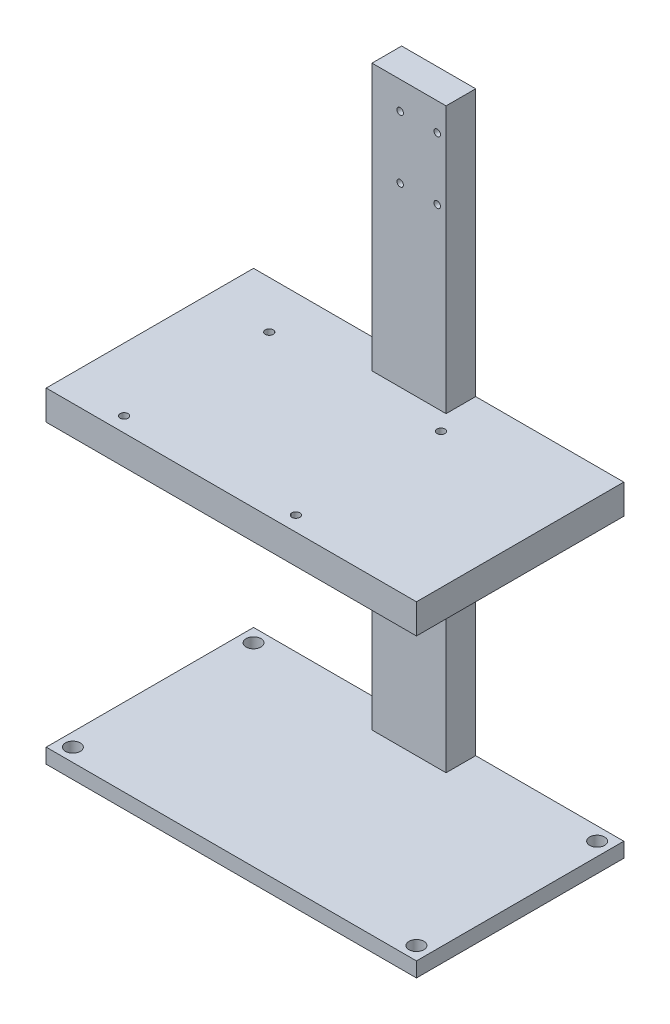
SolidWorks part; units mm, degrees
ref_plane "Front Plane" through (0, 0, 0) normal (0, 0, 1) x (1, 0, 0)
ref_plane "Top Plane" through (0, 0, 0) normal (0, 1, 0) x (1, 0, 0)
ref_plane "Right Plane" through (0, 0, 0) normal (1, 0, 0) x (0, 0, -1)
sketch "Sketch2" plane through (0, 0, 0) normal (0, 0, 1) x (1, 0, 0)
  line L1 (-80.8946, 1.3413) -> (-55.8946, 1.3413)
  line L2 (-80.8946, 1.3413) -> (-80.8946, -98.6587)
  line L3 (-80.8946, -98.6587) -> (-55.8946, -98.6587)
  line L4 (-55.8946, 1.3413) -> (-55.8946, -98.6587)
  line L5 (-80.8946, -98.6587) -> (-55.8946, -98.6587)
  line L6 (-80.8946, -98.6587) -> (-80.8946, -198.6587)
  line L7 (-80.8946, -198.6587) -> (-55.8946, -198.6587)
  line L8 (-130.8946, -88.6587) -> (-5.8946, -88.6587)
  line L9 (-130.8946, -88.6587) -> (-130.8946, -98.6587)
  line L10 (-130.8946, -98.6587) -> (-5.8946, -98.6587)
  line L11 (-5.8946, -88.6587) -> (-5.8946, -98.6587)
  line L12 (-55.8946, -98.6587) -> (-55.8946, -198.6587)
  circle A0 centre (-71.3946, -8.0207) radius 1.1
  circle A1 centre (-58.8946, -8.0207) radius 1.1
  circle A2 centre (-71.3946, -29.0207) radius 1.1
  circle A3 centre (-58.8946, -29.0207) radius 1.1
  point P16 (0, 0)
  point P20 (0, 0)
  dimension "D7" = 2.2
  dimension "D8" = 2.2
  dimension "D12" = 2.2
  dimension "D13" = 2.2
  dimension "D1" = 25
  dimension "D2" = 100
  dimension "D3" = 50
  dimension "D4" = 125
  dimension "D5" = 10
  dimension "D6" = 0
  dimension "D9" = 15.5
  dimension "D10" = 3
  dimension "D11" = 15.5
  dimension "D14" = 21
  dimension "D15" = 21
  dimension "D16" = 100
  dimension "D17" = 25
  dimension "D18" = 3
extrude "Boss-Extrude3" add sketch "Sketch2" along normal blind 10 contours L2 L8 L4 L1 A3 A2 A1 A0 | L12 L3 L6 L7 | L8 L2 L3 L4 | L9 L10 L2 L8
sketch "Sketch5" plane through (0, 0, 10) normal (0, 0, 1) x (1, 0, 0)
  line L1 (-130.8946, -88.6587) -> (-5.8946, -88.6587)
  line L2 (-130.8946, -88.6587) -> (-130.8946, -98.6587)
  line L3 (-130.8946, -98.6587) -> (-5.8946, -98.6587)
  line L4 (-5.8946, -88.6587) -> (-5.8946, -98.6587)
extrude "Boss-Extrude4" add sketch "Sketch5" along normal blind 60
sketch "Sketch6" plane through (0, 0, 10) normal (0, 0, 1) x (1, 0, 0)
  line L1 (-55.8946, -198.6587) -> (-130.8946, -198.6587)
  line L2 (-55.8946, -198.6587) -> (-55.8946, -193.6587)
  line L3 (-55.8946, -193.6587) -> (-130.8946, -193.6587)
  line L4 (-130.8946, -198.6587) -> (-130.8946, -193.6587)
  line L5 (-80.8946, -98.6587) -> (-80.8946, -198.6587) construction
  line L6 (-55.8946, -98.6587) -> (-55.8946, -198.6587) construction
  line L7 (-80.8946, -198.6587) -> (-5.8946, -198.6587)
  line L8 (-80.8946, -198.6587) -> (-80.8946, -193.6587)
  line L9 (-80.8946, -193.6587) -> (-5.8946, -193.6587)
  line L10 (-5.8946, -198.6587) -> (-5.8946, -193.6587)
  point P14 (0, 0)
  point P15 (0, 0)
  point P16 (0, 0)
  dimension "D1" = 5
  dimension "D2" = 50
  dimension "D3" = 5
  dimension "D4" = 50
extrude "Boss-Extrude5" add sketch "Sketch6" along normal blind 60 contours L9 L10 L7 L8
sketch "Sketch7" plane through (-80.8946, 0, 0) normal (-1, 0, 0) x (0, 0, 1)
  line L1 (70, -198.6587) -> (0, -198.6587)
  line L2 (70, -198.6587) -> (70, -193.6587)
  line L3 (70, -193.6587) -> (0, -193.6587)
  line L4 (0, -198.6587) -> (0, -193.6587)
  dimension "D1" = 5
sketch "Sketch8" plane through (-55.8946, 0, 0) normal (1, 0, 0) x (0, 0, -1)
  line L0 (-10, -193.6587) -> (-10, -198.6587) construction
  line L1 (0, -198.6587) -> (-10, -198.6587)
  line L2 (0, -198.6587) -> (0, -193.6587)
  line L3 (0, -193.6587) -> (-10, -193.6587)
  line L4 (-10, -198.6587) -> (-10, -193.6587)
extrude "Boss-Extrude7" add sketch "Sketch8" along normal blind 50
sketch "Sketch11" plane through (-80.8946, 0, 0) normal (-1, 0, 0) x (0, 0, 1)
extrude "Boss-Extrude8" add sketch "Sketch7" along normal blind 50
sketch "Sketch12" plane through (0, -193.6587, 0) normal (0, 1, 0) x (1, 0, 0)
  line L0 (-130.8946, -70) -> (-130.8946, 0) construction
  line L1 (-130.8946, 0) -> (-80.8946, 0) construction
  line L2 (-130.8946, -70) -> (-5.8946, -70) construction
  line L3 (-5.8946, -70) -> (-5.8946, 0) construction
  circle A0 centre (-126.3946, -4.5) radius 2.5
  circle A1 centre (-126.3946, -65.5) radius 2.5
  circle A2 centre (-10.3946, -65.5) radius 2.5
  circle A3 centre (-10.3946, -4.5) radius 2.5
  dimension "D1" = 5
  dimension "D4" = 5
  dimension "D7" = 5
  dimension "D10" = 5
  dimension "D2" = 4.5
  dimension "D3" = 4.5
  dimension "D5" = 4.5
  dimension "D6" = 4.5
  dimension "D8" = 4.5
  dimension "D9" = 4.5
  dimension "D11" = 4.5
extrude "Cut-Extrude1" cut sketch "Sketch12" against normal through all
sketch "Sketch13" plane through (0, -88.6587, 0) normal (0, 1, 0) x (1, 0, 0)
  line L0 (-5.8946, -70) -> (-130.8946, -70) construction
  line L1 (-130.8946, -70) -> (-130.8946, 0) construction
  circle A0 centre (-109.5946, -16) radius 1.35
  circle A1 centre (-109.5946, -65) radius 1.35
  circle A2 centre (-51.5946, -65) radius 1.35
  circle A3 centre (-51.5946, -16) radius 1.35
  point P8 (0, 0)
  point P9 (0, 0)
  point P10 (-38.1647, -55.3102)
  point P11 (0, 0)
  point P12 (0, 0)
  point P13 (0, 0)
  point P14 (0, 0)
  dimension "D1" = 2.7
  dimension "D2" = 2.7
  dimension "D3" = 2.7
  dimension "D4" = 2.7
  dimension "D5" = 58
  dimension "D6" = 58
  dimension "D7" = 49
  dimension "D8" = 49
  dimension "D9" = 5
  dimension "D10" = 21.3
  dimension "D11" = 21.3
extrude "Cut-Extrude2" cut sketch "Sketch13" against normal up to next
